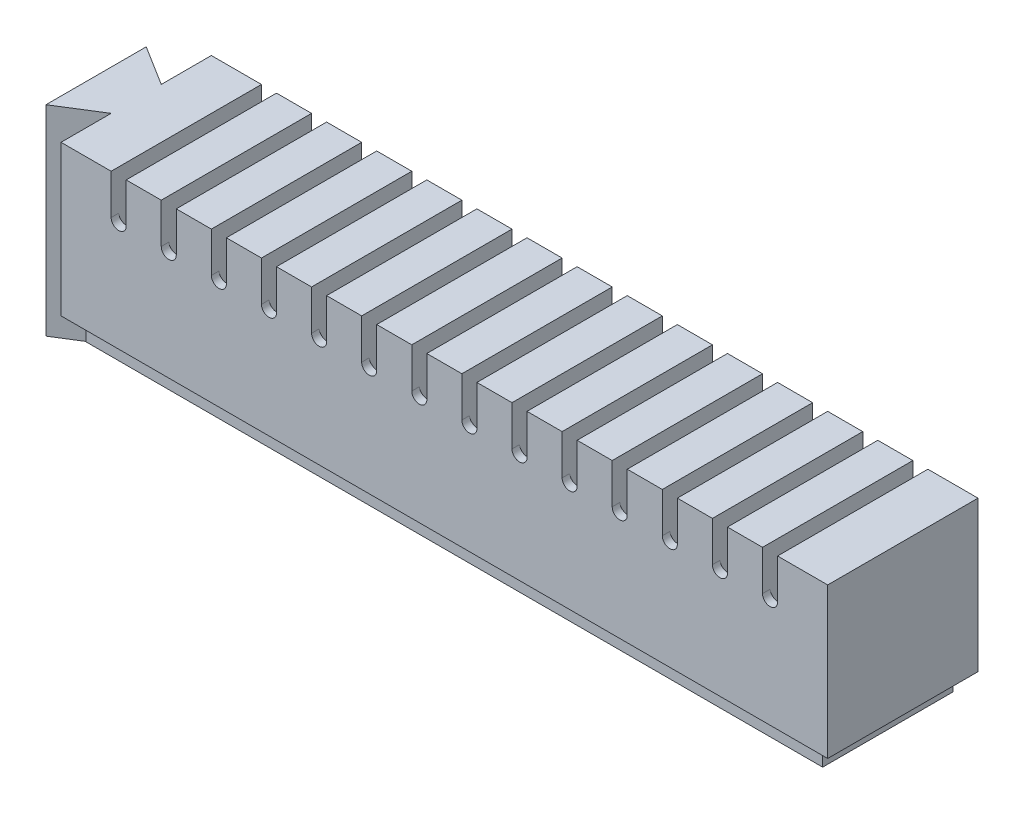
SolidWorks part; units mm, degrees
ref_plane "Front Plane" through (0, 0, 0) normal (0, 0, 1) x (1, 0, 0)
ref_plane "Top Plane" through (0, 0, 0) normal (0, 1, 0) x (1, 0, 0)
ref_plane "Right Plane" through (0, 0, 0) normal (1, 0, 0) x (0, 0, -1)
sketch "Sketch1" plane through (0, 0, 0) normal (0, 1, 0) x (1, 0, 0)
  line L1 (0, 0) -> (3.5, 0)
  line L2 (0, 0) -> (0, 15)
  line L3 (0, 15) -> (3.5, 15)
  line L4 (3.5, 0) -> (3.5, 15)
  dimension "D1" = 15
  dimension "D2" = 3.5
extrude "Boss-Extrude1" add sketch "Sketch1" along normal blind 15
sketch "Sketch2" plane through (0, 0, 0) normal (0, -1, 0) x (1, 0, 0)
  line L0 (0, 0) -> (3.5, 0) construction
  line L1 (1, -2) -> (2.5, -2)
  line L2 (1, -2) -> (1, -13)
  line L3 (1, -13) -> (2.5, -13)
  line L4 (2.5, -2) -> (2.5, -13)
  line L6 (3.5, -15) -> (0, -15) construction
  line L7 (0, -15) -> (0, 0) construction
  line L8 (3.5, 0) -> (3.5, -15) construction
  dimension "D1" = 2
  dimension "D2" = 2
  dimension "D3" = 1
  dimension "D4" = 1
extrude "Cut-Extrude1" cut sketch "Sketch2" against normal offset from surface (13 mm away) 2 up to face at (1.75, 15, -7.5)
sketch "Sketch3" plane through (0, 0, 0) normal (-1, 0, 0) x (0, 0, 1)
  line L0 (0, 15) -> (0, 0) construction
  line L1 (-15, 0) -> (0, 0)
  line L2 (-15, 0) -> (-15, 3)
  line L3 (-15, 3) -> (0, 3)
  line L4 (0, 0) -> (0, 3)
extrude "Boss-Extrude2" add sketch "Sketch3" along normal blind 1.5
pattern_linear "LPattern1" count 15 spacing 5 along (1, 0, 0) of bodies 103
combine bodies "Combine1" operation type add bodies to combine 104 105 106 107 108 109 110 111 112 113 114 115 116 117 103
sketch "Sketch4" plane through (73.5, 0, 0) normal (1, 0, 0) x (0, 0, -1)
  line L1 (0, 15) -> (15, 15)
  line L2 (0, 15) -> (0, 0)
  line L3 (0, 0) -> (15, 0)
  line L4 (15, 15) -> (15, 0)
extrude "Boss-Extrude3" add sketch "Sketch4" along normal blind 1.5
sketch "Sketch5" plane through (0, 0, 0) normal (-1, 0, 0) x (0, 0, 1)
  line L1 (-15, 15) -> (0, 15)
  line L2 (-15, 15) -> (-15, 3)
  line L3 (-15, 3) -> (0, 3)
  line L4 (0, 15) -> (0, 3)
extrude "Boss-Extrude4" add sketch "Sketch5" along normal blind 1.5
sketch "Sketch7" plane through (0, 0, 0) normal (0, -1, 0) x (1, 0, 0)
  line L3 (71, -2) -> (71, -13) construction
  line L4 (2.5, -6.5) -> (71, -6.5)
  line L5 (2.5, -6.5) -> (2.5, -8.5)
  line L6 (2.5, -8.5) -> (71, -8.5)
  line L7 (71, -6.5) -> (71, -8.5)
  line L8 (2.5, -6.5) -> (71, -8.5) construction
  line L9 (2.5, -8.5) -> (71, -6.5) construction
  point P8 (36.75, -7.5)
extrude "Cut-Extrude2" cut sketch "Sketch7" against normal blind 2
sketch "Sketch8" plane through (0, 0, 0) normal (0, -1, 0) x (-1, 0, 0)
  line L0 (-72.5, 13) -> (-72.5, 2) construction
  line L1 (-1, 2) -> (-72.5, 2)
  line L2 (-1, 2) -> (-1, 13)
  line L3 (-1, 13) -> (-72.5, 13)
  line L4 (-72.5, 2) -> (-72.5, 13)
  line L5 (0, 1) -> (0, 14)
  line L6 (0, 14) -> (-73.5, 14)
  line L7 (-73.5, 1) -> (-73.5, 14)
  line L8 (0, 1) -> (-73.5, 1)
  dimension "D1" = 1
extrude "Boss-Extrude5" add sketch "Sketch8" along normal blind 2
sketch "Sketch9" plane through (0, 0, 0) normal (0, -1, 0) x (1, 0, 0)
  line L0 (2.5, -13) -> (6, -13) construction
  line L1 (6, -13) -> (6, -8.5) construction
  line L2 (6, -8.5) -> (2.5, -8.5) construction
  line L3 (2.5, -8.5) -> (2.5, -13) construction
  line L4 (6, -2) -> (2.5, -2) construction
  line L5 (2.5, -2) -> (2.5, -6.5) construction
  line L6 (2.5, -6.5) -> (6, -6.5) construction
  line L7 (6, -6.5) -> (6, -2) construction
  line L8 (2.5, -13) -> (6, -13) construction
  line L9 (6, -13) -> (6, -8.5) construction
  line L10 (6, -8.5) -> (2.5, -8.5) construction
  line L11 (2.5, -8.5) -> (2.5, -13) construction
  line L12 (6, -2) -> (2.5, -2) construction
  line L13 (2.5, -2) -> (2.5, -6.5) construction
  line L14 (2.5, -6.5) -> (6, -6.5) construction
  line L15 (6, -6.5) -> (6, -2) construction
  line L24 (5, -3) -> (3.5, -3)
  line L25 (3.5, -3) -> (3.5, -5.5)
  line L26 (3.5, -5.5) -> (5, -5.5)
  line L27 (5, -5.5) -> (5, -3)
  line L28 (5, -3) -> (3.5, -3)
  line L29 (3.5, -3) -> (3.5, -5.5)
  line L30 (3.5, -5.5) -> (5, -5.5)
  line L31 (5, -5.5) -> (5, -3)
  line L36 (3.5, -12) -> (5, -12)
  line L37 (5, -12) -> (5, -9.5)
  line L38 (5, -9.5) -> (3.5, -9.5)
  line L39 (3.5, -9.5) -> (3.5, -12)
  line L40 (3.5, -12) -> (5, -12)
  line L41 (5, -12) -> (5, -9.5)
  line L42 (5, -9.5) -> (3.5, -9.5)
  line L43 (3.5, -9.5) -> (3.5, -12)
  dimension "D1" = 1
  dimension "D2" = 1
extrude "Boss-Extrude6" add sketch "Sketch9" along normal blind 2
pattern_linear "LPattern2" count 14 spacing 5 along (1, 0, 0) of "Boss-Extrude6"
sketch "Sketch17" plane through (70, 0, 0) normal (-1, 0, 0) x (0, 0, 1)
  line L0 (-7.5, 15) -> (-7.5, -49985) construction
  line L1 (-15, 15) -> (0, 15) construction
  line L2 (-15, 11) -> (-14.25, 11)
  line L3 (-15, 15) -> (-15, 3) construction
  line L4 (-14.25, 11) -> (-13.5, 3)
  line L5 (0, 3) -> (-15, 3) construction
  line L6 (-13.5, 3) -> (-15, 3)
  line L7 (-15, 3) -> (-15, 11)
  line L8 (0, 3) -> (0, 11)
  line L9 (-1.5, 3) -> (0, 3)
  line L10 (-0.75, 11) -> (-1.5, 3)
  line L11 (0, 11) -> (-0.75, 11)
  point P4 (-7.5, 15)
  dimension "D1" = 0.75
  dimension "D2" = 1.5
  dimension "D3" = 4
extrude "Boss-Extrude12" add sketch "Sketch17" along normal blind 1.5
sketch "Sketch18" plane through (0, 0, -15) normal (0, 0, -1) x (-1, 0, 0)
  line L0 (-68.5, 11) -> (-70, 11) construction
  circle A0 centre (-69.25, 11) radius 0.75
extrude "Cut-Extrude3" cut sketch "Sketch18" against normal through all
pattern_linear "LPattern4" count 14 spacing 5 along (-1, 0, 0) of "Boss-Extrude12", "Cut-Extrude3"
sketch "Sketch19" plane through (0, 15, 0) normal (0, 1, 0) x (1, 0, 0)
  line L0 (-1.5, 7.5) -> (49998.5, 7.5) construction
  line L1 (-1.5, 0) -> (-1.5, 15) construction
  line L2 (-1.5, 5) -> (-5.5, 2.5)
  line L3 (-5.5, 2.5) -> (-5.5, 12.5)
  line L4 (-5.5, 12.5) -> (-1.5, 10)
  line L5 (-1.5, 10) -> (-1.5, 5)
  point P4 (-1.5, 7.5)
  dimension "D1" = 5
  dimension "D2" = 10
  dimension "D3" = 4
extrude "Boss-Extrude13" add sketch "Sketch19" against normal blind 20
